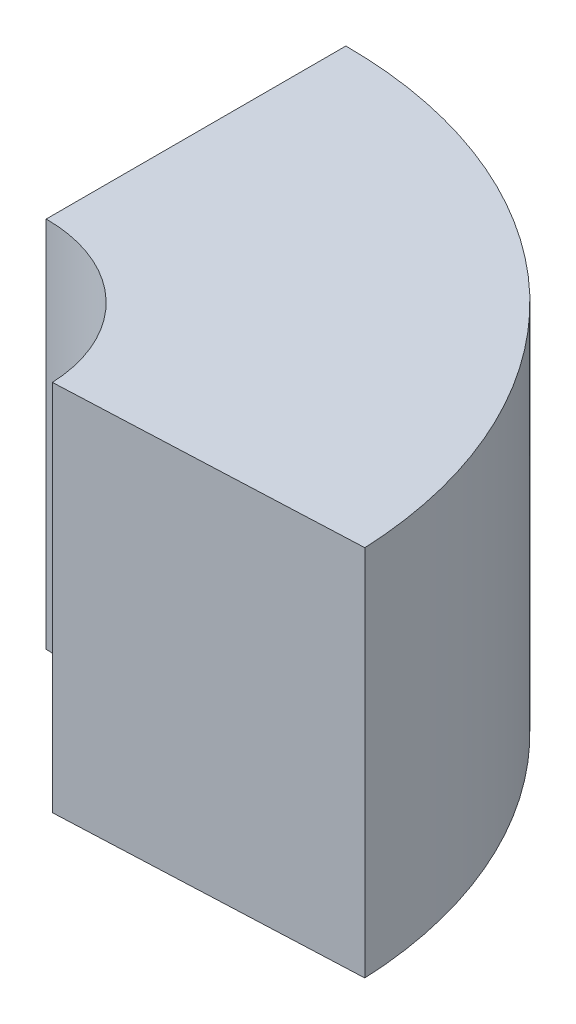
SolidWorks part; units mm, degrees
ref_plane "Front Plane" through (0, 0, 0) normal (0, 0, 1) x (1, 0, 0)
ref_plane "Top Plane" through (0, 0, 0) normal (0, 1, 0) x (1, 0, 0)
ref_plane "Right Plane" through (0, 0, 0) normal (1, 0, 0) x (0, 0, -1)
sketch "RevolveSketch" plane through (0, 0, 0) normal (1, 0, 0) x (0, 0, -1)
  line L1 (20.6, -16.9) -> (44, -16.9)
  line L2 (20.6, -16.9) -> (20.6, 12.2)
  line L3 (20.6, 12.2) -> (44, 12.2)
  line L4 (44, -16.9) -> (44, 12.2)
  line L5 (9.3, -21.9) -> (9.3, 20.2) construction
revolve "OrdinaryBossRevolve" add sketch "RevolveSketch" angle 87.5 about L5
